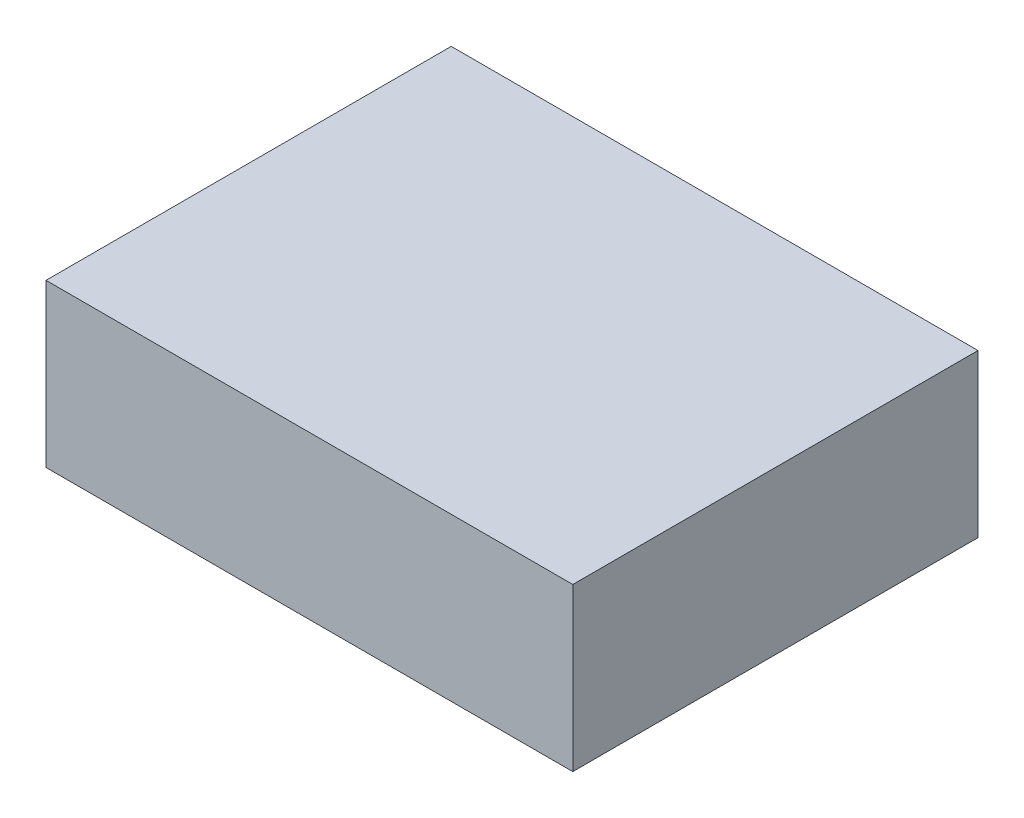
SolidWorks part; units mm, degrees
ref_plane "前视基准面" through (0, 0, 0) normal (0, 0, 1) x (1, 0, 0)
ref_plane "上视基准面" through (0, 0, 0) normal (0, 1, 0) x (1, 0, 0)
ref_plane "右视基准面" through (0, 0, 0) normal (1, 0, 0) x (0, 0, -1)
other "Configuration Table"
sketch "草图1" plane through (0, 0, 0) normal (0, 1, 0) x (1, 0, 0)
  line L1 (-32.5, 25) -> (32.5, 25)
  line L2 (-32.5, 25) -> (-32.5, -25)
  line L3 (-32.5, -25) -> (32.5, -25)
  line L4 (32.5, 25) -> (32.5, -25)
  line L5 (-32.5, 25) -> (32.5, -25) construction
  line L6 (-32.5, -25) -> (32.5, 25) construction
  point P0 (0, 0)
  dimension "D1" = 65
  dimension "D2" = 50
extrude "凸台-拉伸1" add sketch "草图1" along normal blind 20
sketch "草图2" plane through (0, 0, 0) normal (0, -1, 0) x (1, 0, 0)
  text T0 "摄像头" font "宋体" height 3.5
